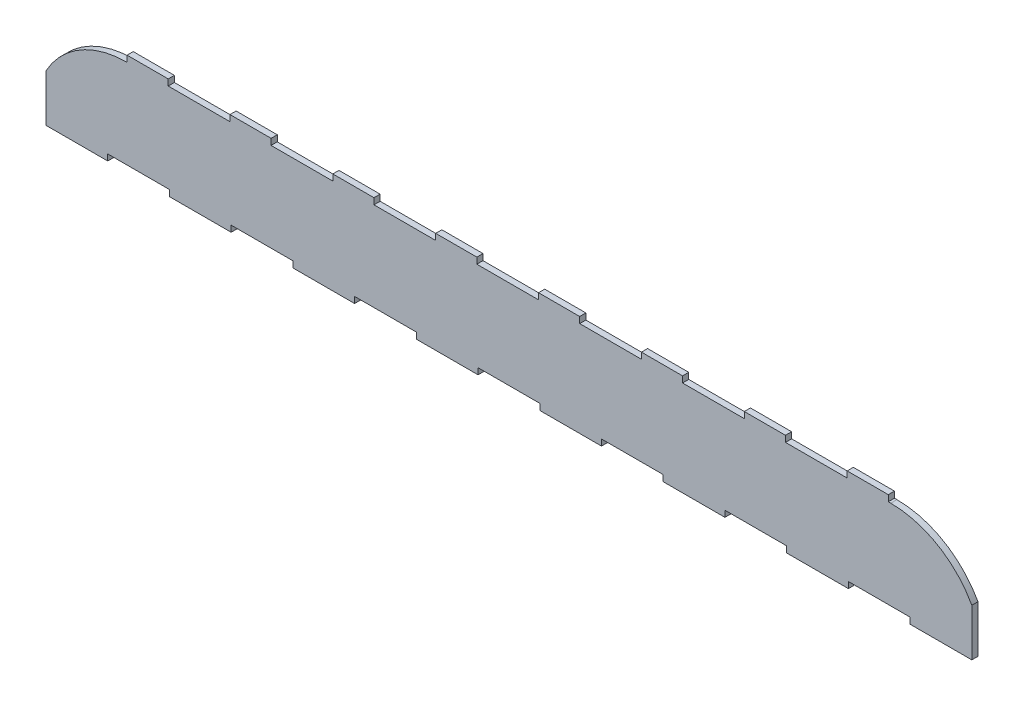
SolidWorks part; units mm, degrees
material "Mahogany"
ref_plane "Front Plane" through (0, 0, 0) normal (0, 0, 1) x (1, 0, 0)
ref_plane "Top Plane" through (0, 0, 0) normal (0, 1, 0) x (1, 0, 0)
ref_plane "Right Plane" through (0, 0, 0) normal (1, 0, 0) x (0, 0, -1)
sketch "Sketch2" plane through (0, 0, 0) normal (0, 0, 1) x (1, 0, 0)
  line L0 (15.2239, 33.5962) -> (15.2239, -9.3746) construction
  line L7 (-209.7761, -9.3746) -> (-209.7761, 10.6254)
  line L8 (-216.4326, -18.5258) -> (-216.4326, -18.5257)
  line L9 (240.2239, -9.3746) -> (240.2239, 10.6254)
  line L10 (-209.7761, -9.3746) -> (240.2239, -9.3746)
  line L11 (-170.3743, 33.8884) -> (200.8221, 33.8884)
  arc A0 (-170.3743, 33.8884) -> (-209.7761, 10.6254) centre (-170.3743, -11.1116) ccw
  arc A1 (200.8221, 33.8884) -> (240.2239, 10.6254) centre (200.8221, -11.1116) cw
  point P0 (0, 0)
  point P4 (15.2239, -9.3746)
  point P18 (15.2239, -9.3746)
  dimension "D2" = 45
  dimension "D3" = 20
  dimension "D4" = 45
  dimension "D5" = 48
  dimension "D6" = 450
  dimension "D7" = 48
  dimension "D1" = 20
extrude "Boss-Extrude1" add sketch "Sketch2" along normal mid plane 3
sketch "Sketch3" plane through (0, 0, 1.5) normal (0, 0, 1) x (1, 0, 0)
  line L0 (-149.7761, -9.3746) -> (-119.7761, -9.3746)
  line L1 (-209.7761, -9.3746) -> (-179.7761, -9.3746)
  line L2 (-209.7761, -9.3746) -> (-209.7761, -12.3746)
  line L3 (-209.7761, -12.3746) -> (-179.7761, -12.3746)
  line L4 (-179.7761, -9.3746) -> (-179.7761, -12.3746)
  line L5 (-149.7761, -9.3746) -> (-149.7761, -12.3746)
  line L6 (-149.7761, -12.3746) -> (-119.7761, -12.3746)
  line L7 (-119.7761, -9.3746) -> (-119.7761, -12.3746)
  line L8 (-89.7761, -9.3746) -> (-59.7761, -9.3746)
  line L9 (-89.7761, -9.3746) -> (-89.7761, -12.3746)
  line L10 (-89.7761, -12.3746) -> (-59.7761, -12.3746)
  line L11 (-59.7761, -9.3746) -> (-59.7761, -12.3746)
  line L12 (-29.7761, -9.3746) -> (0.2239, -9.3746)
  line L13 (-29.7761, -9.3746) -> (-29.7761, -12.3746)
  line L14 (-29.7761, -12.3746) -> (0.2239, -12.3746)
  line L15 (0.2239, -9.3746) -> (0.2239, -12.3746)
  line L16 (30.2239, -9.3746) -> (60.2239, -9.3746)
  line L17 (30.2239, -9.3746) -> (30.2239, -12.3746)
  line L18 (30.2239, -12.3746) -> (60.2239, -12.3746)
  line L19 (60.2239, -9.3746) -> (60.2239, -12.3746)
  line L20 (90.2239, -9.3746) -> (120.2239, -9.3746)
  line L21 (90.2239, -9.3746) -> (90.2239, -12.3746)
  line L22 (90.2239, -12.3746) -> (120.2239, -12.3746)
  line L23 (120.2239, -9.3746) -> (120.2239, -12.3746)
  line L24 (150.2239, -9.3746) -> (180.2239, -9.3746)
  line L25 (150.2239, -9.3746) -> (150.2239, -12.3746)
  line L26 (150.2239, -12.3746) -> (180.2239, -12.3746)
  line L27 (180.2239, -9.3746) -> (180.2239, -12.3746)
  line L28 (210.2239, -9.3746) -> (240.2239, -9.3746)
  line L29 (210.2239, -9.3746) -> (210.2239, -12.3746)
  line L30 (210.2239, -12.3746) -> (240.2239, -12.3746)
  line L31 (240.2239, -9.3746) -> (240.2239, -12.3746)
  dimension "D1" = 30
  dimension "D2" = 3
extrude "Boss-Extrude2" add sketch "Sketch3" against normal blind 3
sketch "Sketch5" plane through (0, 0, 1.5) normal (0, 0, 1) x (1, 0, 0)
  line L0 (-170.3743, 33.8884) -> (-170.3743, 36.8884)
  line L1 (-170.3743, 36.8884) -> (-150.3743, 36.8884)
  line L2 (-150.3743, 36.8884) -> (-150.3743, 33.8884)
  line L3 (-170.3743, 33.8884) -> (200.8221, 33.8884) construction
  line L4 (-120.3743, 33.8884) -> (-120.3743, 36.8884)
  line L5 (-120.3743, 36.8884) -> (-100.3743, 36.8884)
  line L6 (-100.3743, 36.8884) -> (-100.3743, 33.8884)
  line L7 (-70.3743, 33.8884) -> (-70.3743, 36.8884)
  line L8 (-70.3743, 36.8884) -> (-50.3743, 36.8884)
  line L9 (-50.3743, 36.8884) -> (-50.3743, 33.8884)
  line L10 (-20.3743, 33.8884) -> (-20.3743, 36.8884)
  line L11 (-20.3743, 36.8884) -> (-0.3743, 36.8884)
  line L12 (-0.3743, 36.8884) -> (-0.3743, 33.8884)
  line L13 (29.6257, 33.8884) -> (29.6257, 36.8884)
  line L14 (29.6257, 36.8884) -> (49.6257, 36.8884)
  line L15 (49.6257, 36.8884) -> (49.6257, 33.8884)
  line L16 (79.6257, 33.8884) -> (79.6257, 36.8884)
  line L17 (79.6257, 36.8884) -> (99.6257, 36.8884)
  line L18 (99.6257, 36.8884) -> (99.6257, 33.8884)
  line L19 (129.6257, 33.8884) -> (129.6257, 36.8884)
  line L20 (129.6257, 36.8884) -> (149.6257, 36.8884)
  line L21 (149.6257, 36.8884) -> (149.6257, 33.8884)
  line L22 (179.6257, 33.8884) -> (179.6257, 36.8884)
  line L23 (179.6257, 36.8884) -> (199.6257, 36.8884)
  line L24 (199.6257, 36.8884) -> (199.6257, 33.8884)
  line L25 (-170.3743, 33.8884) -> (-150.3743, 33.8884)
  line L26 (-120.3743, 33.8884) -> (-100.3743, 33.8884)
  line L27 (-70.3743, 33.8884) -> (-50.3743, 33.8884)
  line L28 (-20.3743, 33.8884) -> (-0.3743, 33.8884)
  line L29 (29.6257, 33.8884) -> (49.6257, 33.8884)
  line L30 (79.6257, 33.8884) -> (99.6257, 33.8884)
  line L31 (129.6257, 33.8884) -> (149.6257, 33.8884)
  line L32 (179.6257, 33.8884) -> (199.6257, 33.8884)
  dimension "D1" = 3
  dimension "D2" = 20
  dimension "D3" = 30
  dimension "D4" = 7
  dimension "D5" = 30
  dimension "D6" = 2
other "AlignGroup1"
extrude "Boss-Extrude3" add sketch "Sketch5" against normal blind 3
